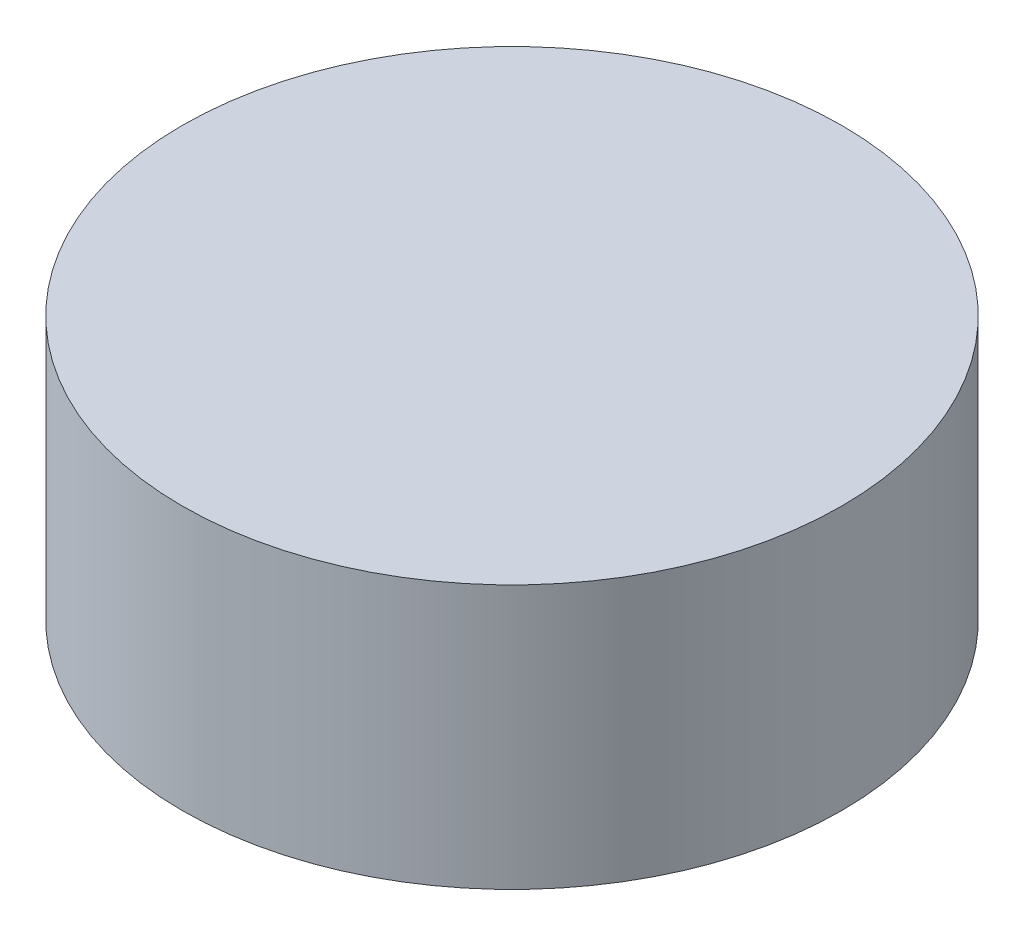
SolidWorks part; units mm, degrees
ref_plane "Płaszczyzna przednia" through (0, 0, 0) normal (0, 0, 1) x (1, 0, 0)
ref_plane "Płaszczyzna górna" through (0, 0, 0) normal (0, 1, 0) x (1, 0, 0)
ref_plane "Płaszczyzna prawa" through (0, 0, 0) normal (1, 0, 0) x (0, 0, -1)
sketch "Szkic1" plane through (0, 0, 0) normal (0, 0, 1) x (1, 0, 0)
  line L0 (0, -3.2878) -> (0, -43.2878) construction
  line L1 (0, -43.2878) -> (-50, -43.2878)
  line L2 (-50, -43.2878) -> (-50, -3.2878)
  line L3 (-50, -3.2878) -> (0, -3.2878)
  line L4 (0, -3.2878) -> (0, -43.2878)
  dimension "D1" = 40
  dimension "D2" = 50
revolve "Obrót1" add sketch "Szkic1" angle 360 about L0
